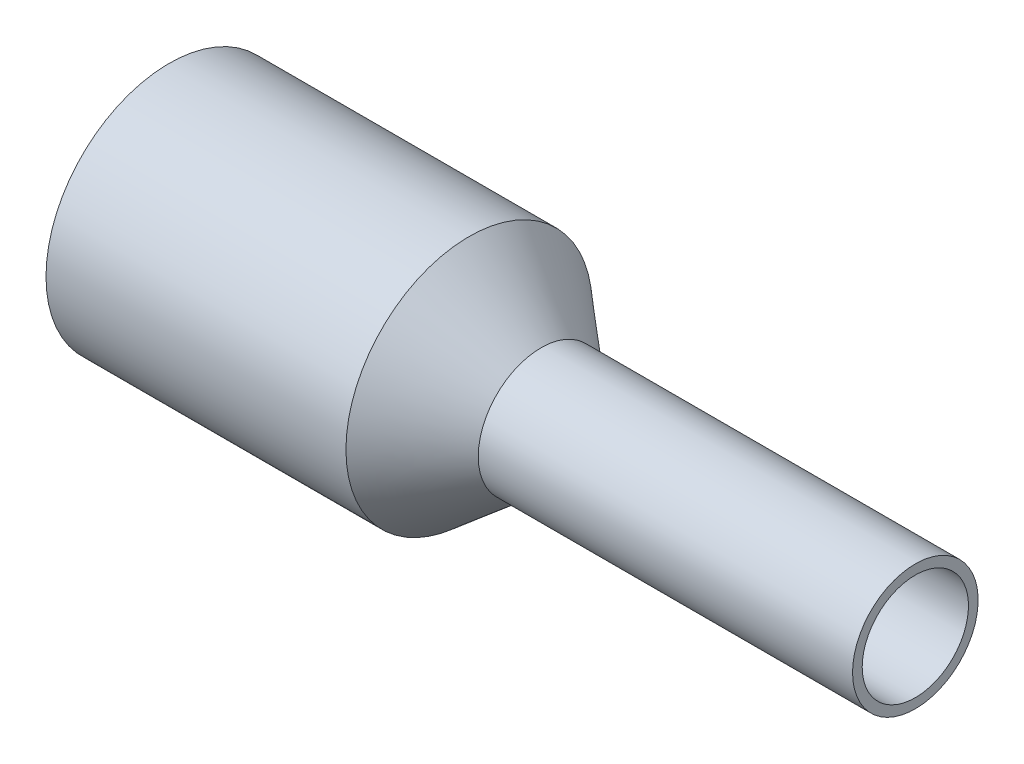
SolidWorks part; units mm, degrees
material "EPDM"
ref_plane "Alzado" through (0, 0, 0) normal (0, 0, 1) x (1, 0, 0)
ref_plane "Planta" through (0, 0, 0) normal (0, 1, 0) x (1, 0, 0)
ref_plane "Vista lateral" through (0, 0, 0) normal (1, 0, 0) x (0, 0, -1)
sketch "Croquis1" plane through (0, 0, 0) normal (0, 0, 1) x (1, 0, 0)
  line L0 (-7.725, 0) -> (7.725, 0) construction
  line L1 (7.725, 1.1) -> (-0.025, 1.1)
  line L2 (7.725, 1.1) -> (7.725, 0) construction
  line L3 (-7.725, 2.05) -> (-1.1572, 2.05) construction
  line L4 (-1.1572, 2.05) -> (-0.025, 1.1) construction
  line L5 (7.725, 1.1) -> (7.725, 1.3)
  line L6 (7.725, 1.3) -> (-0.025, 1.3)
  line L7 (-7.725, 2.05) -> (-7.725, 2.55)
  line L8 (-7.725, 2.55) -> (-1.5147, 2.55)
  line L9 (-1.5147, 2.55) -> (-0.025, 1.3)
  line L10 (-7.725, 2.05) -> (-1.5147, 2.05)
  line L11 (-1.5147, 2.05) -> (-0.025, 1.1)
revolve "Revolución1" add sketch "Croquis1" angle 360 about L0
